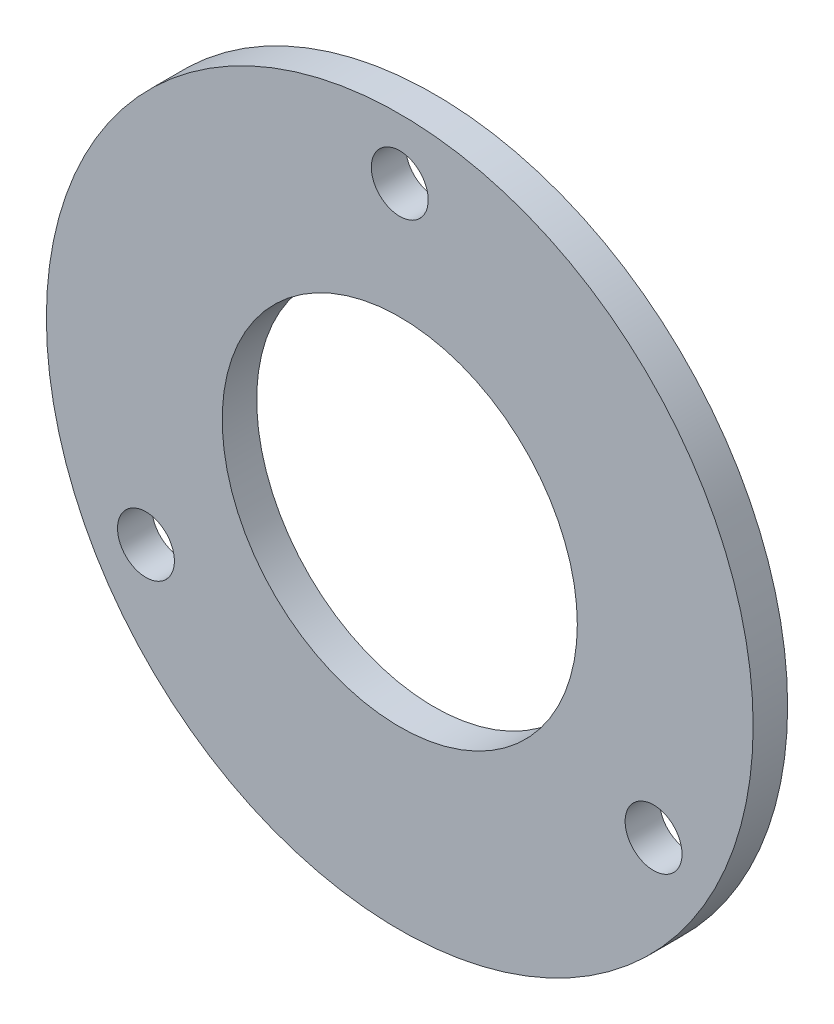
SolidWorks part; units mm, degrees
ref_plane "前视基准面" through (0, 0, 0) normal (0, 0, 1) x (1, 0, 0)
ref_plane "上视基准面" through (0, 0, 0) normal (0, 1, 0) x (1, 0, 0)
ref_plane "右视基准面" through (0, 0, 0) normal (1, 0, 0) x (0, 0, -1)
other "Configuration Table"
sketch "Profile_1" plane through (0, 0, 0) normal (0, 0, 1) x (1, 0, 0)
  circle A0 centre (0, 0) radius 20.5
  circle A1 centre (0, 0) radius 10.3
  circle A2 centre (0, 17) radius 1.65
  circle A3 centre (-14.7224, -8.5) radius 1.65
  circle A4 centre (14.7224, -8.5) radius 1.65
extrude "Outer_race_retainer" add sketch "Profile_1" along normal blind 2 from offset 0
